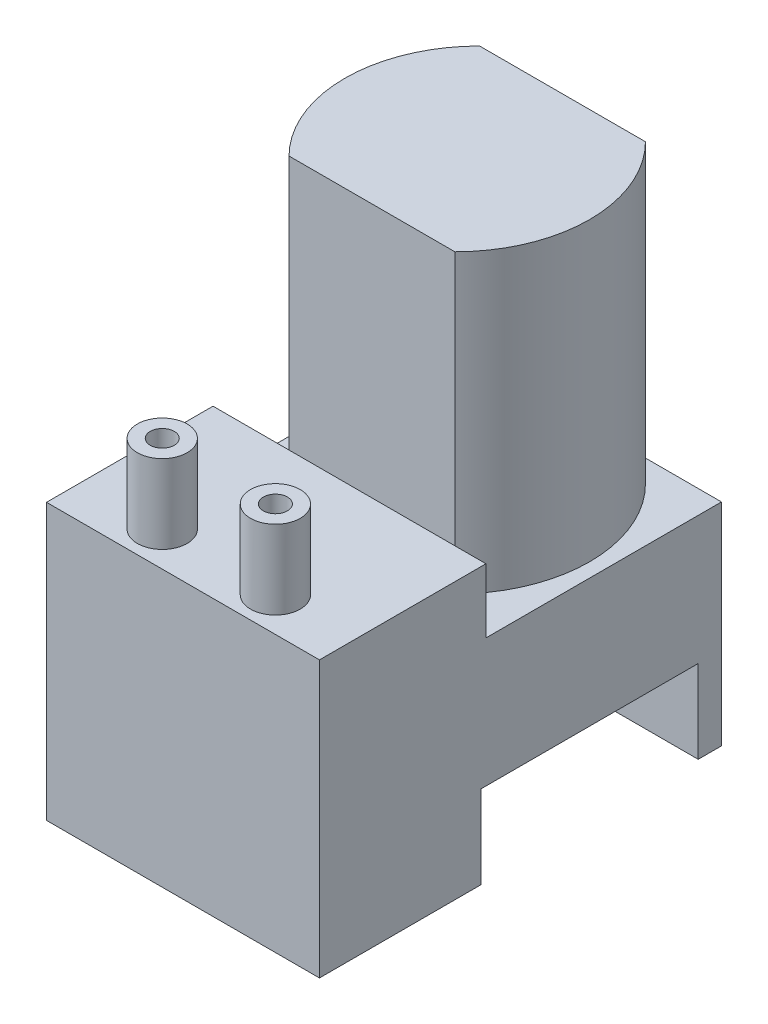
SolidWorks part; units mm, degrees
ref_plane "Front Plane" through (0, 0, 0) normal (0, 0, 1) x (1, 0, 0)
ref_plane "Top Plane" through (0, 0, 0) normal (0, 1, 0) x (1, 0, 0)
ref_plane "Right Plane" through (0, 0, 0) normal (1, 0, 0) x (0, 0, -1)
sketch "Sketch2" plane through (0, 0, 0) normal (0, 0, 1) x (1, 0, 0)
  line L1 (-8.5, 8.58) -> (8.5, 8.58)
  line L2 (-8.5, 8.58) -> (-8.5, -8.58)
  line L3 (-8.5, -8.58) -> (8.5, -8.58)
  line L4 (8.5, 8.58) -> (8.5, -8.58)
  line L5 (-8.5, 8.58) -> (8.5, -8.58) construction
  line L6 (-8.5, -8.58) -> (8.5, 8.58) construction
  point P0 (0, 0)
  dimension "D1" = 17
  dimension "D2" = 17.16
extrude "Boss-Extrude1" add sketch "Sketch2" along normal blind 25.04
sketch "Sketch3" plane through (0, 8.58, 0) normal (0, 1, 0) x (1, 0, 0)
  circle A0 centre (3.6163, -22.9017) radius 1.55
  circle A1 centre (-3.4466, -22.885) radius 1.55
extrude "Boss-Extrude2" add sketch "Sketch3" along normal blind 4.9
sketch "Sketch4" plane through (0, 13.48, 0) normal (0, 1, 0) x (1, 0, 0)
  circle A0 centre (3.6163, -22.9017) radius 0.75
extrude "Cut-Extrude1" cut sketch "Sketch4" against normal blind 4.9
sketch "Sketch6" plane through (0, 13.48, 0) normal (0, 1, 0) x (1, 0, 0)
  circle A0 centre (-3.4466, -22.885) radius 0.75
extrude "Cut-Extrude3" cut sketch "Sketch6" against normal blind 4.9
sketch "Sketch7" plane through (0, -8.58, 0) normal (0, -1, 0) x (1, 0, 0)
  line L0 (-8.5, 25.04) -> (-8.5, 0) construction
  line L1 (8.5, 1.45) -> (-8.5, 1.45)
  line L2 (8.5, 1.45) -> (8.5, 14.97)
  line L3 (8.5, 14.97) -> (-8.5, 14.97)
  line L4 (-8.5, 1.45) -> (-8.5, 14.97)
  line L5 (8.5, 25.04) -> (8.5, 0) construction
  line L6 (-8.5, 0) -> (8.5, 0) construction
  point P4 (-8.1598, 15.2927)
  point P5 (0, 0)
  point P6 (-8.62, 15.4297)
  point P9 (8.62, 2.0286)
  dimension "D1" = 13.52
  dimension "D2" = 1.45
extrude "Cut-Extrude4" cut sketch "Sketch7" against normal blind 5.17
sketch "Sketch8" plane through (-8.5, 0, 0) normal (-1, 0, 0) x (0, 0, 1)
  line L0 (25.04, 8.58) -> (25.04, -8.58) construction
  line L1 (0, 8.58) -> (14.67, 8.58)
  line L2 (0, 8.58) -> (0, 4.58)
  line L3 (0, 4.58) -> (14.67, 4.58)
  line L4 (14.67, 8.58) -> (14.67, 4.58)
  dimension "D1" = 10.37
  dimension "D2" = 4
extrude "Cut-Extrude5" cut sketch "Sketch8" against normal up to next
sketch "Sketch9" plane through (-8.5, 0, 0) normal (-1, 0, 0) x (0, 0, 1)
  line L0 (0, 4.58) -> (14.67, 4.58) construction
  line L1 (1.45, -3.41) -> (14.99, -3.41)
  line L2 (1.45, -3.41) -> (1.45, 2.23)
  line L3 (1.45, 2.23) -> (14.99, 2.23)
  line L4 (14.99, -3.41) -> (14.99, 2.23)
  dimension "D1" = 2.35
  dimension "D2" = 13.54
extrude "Cut-Extrude7" cut sketch "Sketch9" against normal blind 15.01
sketch "Sketch10" plane through (0, 4.58, 0) normal (0, 1, 0) x (1, 0, 0)
  line L8 (5.165, -13.27) -> (-5.165, -13.27)
  line L9 (5.165, -1.4) -> (-5.165, -1.4)
  arc A2 (5.165, -13.27) -> (5.165, -1.4) centre (-0.77, -7.335) ccw
  arc A3 (-5.165, -13.27) -> (-5.165, -1.4) centre (0.77, -7.335) cw
  point P3 (0, -13.27)
  point P11 (0, -7.335)
  point P13 (0, -1.4)
  dimension "D2" = 10.33
  dimension "D3" = 10.33
extrude "Boss-Extrude3" add sketch "Sketch10" along normal blind 18.46
